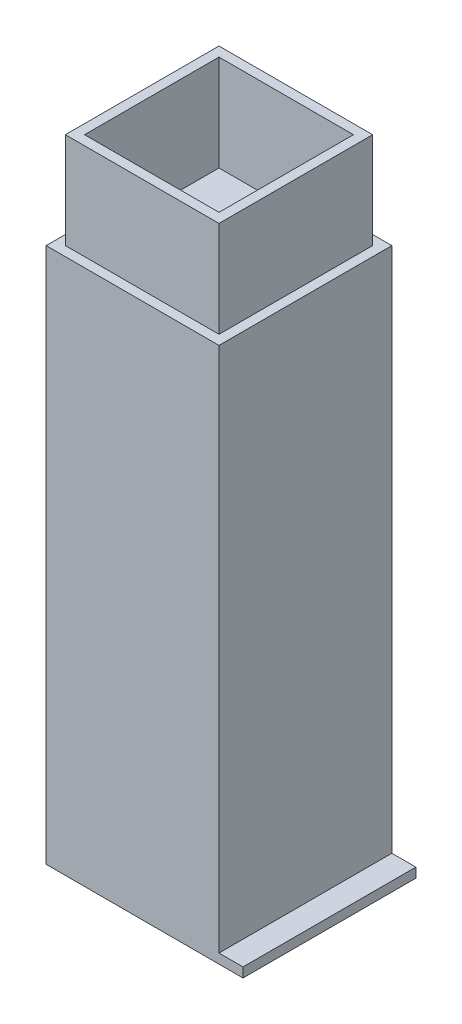
SolidWorks part; units mm, degrees
ref_plane "Front Plane" through (0, 0, 0) normal (0, 0, 1) x (1, 0, 0)
ref_plane "Top Plane" through (0, 0, 0) normal (0, 1, 0) x (1, 0, 0)
ref_plane "Right Plane" through (0, 0, 0) normal (1, 0, 0) x (0, 0, -1)
sketch "Sketch1" plane through (0, 0, 0) normal (0, 1, 0) x (1, 0, 0)
  line L1 (-77.0445, 48.0093) -> (-45.0445, 48.0093)
  line L2 (-77.0445, 48.0093) -> (-77.0445, 16.0093)
  line L3 (-77.0445, 16.0093) -> (-45.0445, 16.0093)
  line L4 (-45.0445, 48.0093) -> (-45.0445, 16.0093)
  line L5 (-79.0445, 50.0093) -> (-43.0445, 50.0093)
  line L6 (-79.0445, 50.0093) -> (-79.0445, 14.0093)
  line L7 (-79.0445, 14.0093) -> (-43.0445, 14.0093)
  line L8 (-43.0445, 50.0093) -> (-43.0445, 14.0093)
  dimension "D1" = 32
  dimension "D2" = 32
  dimension "D3" = 2
  dimension "D4" = 2
  dimension "D5" = 2
  dimension "D6" = 2
extrude "Boss-Extrude1" add sketch "Sketch1" along normal blind 76.2
sketch "Sketch2" plane through (0, 0, 0) normal (0, -1, 0) x (1, 0, 0)
  line L1 (-43.0445, -14.0093) -> (-79.0445, -14.0093)
  line L2 (-43.0445, -14.0093) -> (-43.0445, -50.0093)
  line L3 (-43.0445, -50.0093) -> (-79.0445, -50.0093)
  line L4 (-79.0445, -14.0093) -> (-79.0445, -50.0093)
extrude "Boss-Extrude2" add sketch "Sketch2" along normal blind 5
sketch "Sketch3" plane through (0, -5, 0) normal (0, -1, 0) x (1, 0, 0)
  line L1 (-43.0445, -14.0093) -> (-79.0445, -14.0093)
  line L2 (-43.0445, -14.0093) -> (-43.0445, -50.0093)
  line L3 (-43.0445, -50.0093) -> (-79.0445, -50.0093)
  line L4 (-79.0445, -14.0093) -> (-79.0445, -50.0093)
  line L5 (-77.0445, -16.0093) -> (-45.0445, -16.0093)
  line L6 (-77.0445, -16.0093) -> (-77.0445, -48.0093)
  line L7 (-77.0445, -48.0093) -> (-45.0445, -48.0093)
  line L8 (-45.0445, -16.0093) -> (-45.0445, -48.0093)
  dimension "D3" = 2
  dimension "D1" = 2
  dimension "D2" = 2
  dimension "D6" = 2
extrude "Boss-Extrude3" add sketch "Sketch3" along normal blind 25.4
sketch "Sketch4" plane through (-43.0445, 0, 0) normal (1, 0, 0) x (0, 0, -1)
  line L0 (14.0093, 76.2) -> (14.0093, -30.4) construction
  line L1 (14.0093, -28.4) -> (50.0093, -28.4)
  line L2 (14.0093, -28.4) -> (14.0093, -30.4)
  line L3 (14.0093, -30.4) -> (50.0093, -30.4)
  line L4 (50.0093, -28.4) -> (50.0093, -30.4)
  dimension "D1" = 2
extrude "Boss-Extrude4" add sketch "Sketch4" along normal blind 5
sketch "Sketch5" plane through (0, 76.2, 0) normal (0, 1, 0) x (1, 0, 0)
  line L1 (-79.0445, 50.0093) -> (-43.0445, 50.0093)
  line L2 (-79.0445, 50.0093) -> (-79.0445, 14.0093)
  line L3 (-79.0445, 14.0093) -> (-43.0445, 14.0093)
  line L4 (-43.0445, 50.0093) -> (-43.0445, 14.0093)
extrude "Boss-Extrude5" add sketch "Sketch5" along normal blind 5
sketch "Sketch6" plane through (0, 81.2, 0) normal (0, 1, 0) x (1, 0, 0)
  line L1 (-79.0445, 14.0093) -> (-43.0445, 14.0093)
  line L2 (-79.0445, 14.0093) -> (-79.0445, 50.0093)
  line L3 (-79.0445, 50.0093) -> (-43.0445, 50.0093)
  line L4 (-43.0445, 14.0093) -> (-43.0445, 50.0093)
  line L5 (-77.0445, 16.0093) -> (-45.0445, 16.0093)
  line L6 (-77.0445, 16.0093) -> (-77.0445, 48.0093)
  line L7 (-77.0445, 48.0093) -> (-45.0445, 48.0093)
  line L8 (-45.0445, 16.0093) -> (-45.0445, 48.0093)
  line L9 (-75.0445, 46.0093) -> (-47.0445, 46.0093)
  line L10 (-75.0445, 46.0093) -> (-75.0445, 18.0093)
  line L11 (-75.0445, 18.0093) -> (-47.0445, 18.0093)
  line L12 (-47.0445, 46.0093) -> (-47.0445, 18.0093)
  dimension "D3" = 2
  dimension "D4" = 2
  dimension "D5" = 2
  dimension "D1" = 2
  dimension "D2" = 2
  dimension "D6" = 2
  dimension "D7" = 2
  dimension "D8" = 2
extrude "Boss-Extrude6" add sketch "Sketch6" along normal blind 20 contours L5 L8 L7 L6 L9 L12 L11 L10
equation "\"tolerance\"= 2"
equation "\"length\"= 30"
equation "\"D1@Sketch1\"=\"length\"+\"tolerance\""
equation "\"D2@Sketch1\"=\"length\"+\"tolerance\""
equation "\"protrusion_thickness\"=2"
equation "\"D3@Sketch1\"=\"protrusion_thickness\""
equation "\"D4@Sketch1\"=\"protrusion_thickness\""
equation "\"D5@Sketch1\"=\"protrusion_thickness\""
equation "\"D1@Sketch3\"=\"protrusion_thickness\""
equation "\"D2@Sketch3\"=\"protrusion_thickness\""
equation "\"D3@Sketch3\"=\"protrusion_thickness\""
equation "\"D6@Sketch3\"=\"protrusion_thickness\""
equation "\"D1@Sketch6\"=\"protrusion_thickness\""
equation "\"D2@Sketch6\"=\"protrusion_thickness\""
equation "\"D3@Sketch6\"=\"protrusion_thickness\""
equation "\"D4@Sketch6\"=\"protrusion_thickness\""
equation "\"D5@Sketch6\"=\"protrusion_thickness\""
equation "\"D6@Sketch6\"=\"protrusion_thickness\""
equation "\"D7@Sketch6\"=\"protrusion_thickness\""
equation "\"D8@Sketch6\"=\"protrusion_thickness\""
